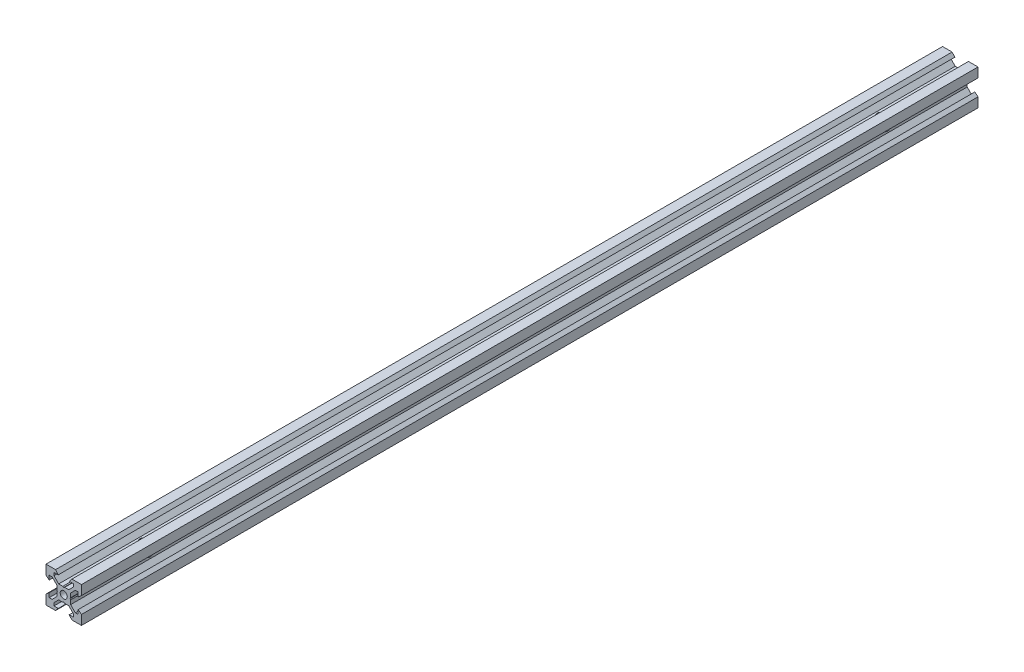
SolidWorks part; units mm, degrees
material "3.3535 (EN-AW 5754)"
ref_plane "Front Plane" through (0, 0, 0) normal (0, 0, 1) x (1, 0, 0)
ref_plane "Top Plane" through (0, 0, 0) normal (0, 1, 0) x (1, 0, 0)
ref_plane "Right Plane" through (0, 0, 0) normal (1, 0, 0) x (0, 0, -1)
sketch "Sketch1" plane through (0, 0, 0) normal (0, 0, 1) x (1, 0, 0)
  line L0 (10, 10) -> (4.6104, 10) construction
  line L1 (10, 10) -> (10, 4.6104) construction
  line L2 (10, -10) -> (10, -4.6104) construction
  line L3 (10, -10) -> (4.6104, -10) construction
  line L4 (10, 10) -> (10, 4.6104)
  line L5 (6.5607, 5.5) -> (8.2, 5.5)
  line L6 (5.5, 8.2) -> (5.5, 6.5607)
  line L7 (10, 10) -> (4.6104, 10)
  line L8 (10, 10) -> (10, 4.6104)
  line L9 (6.5607, 5.5) -> (3.9, 2.8393)
  line L10 (5.5, 6.5607) -> (2.8393, 3.9)
  line L11 (10, 4.6104) -> (8.2, 3.1)
  line L12 (4.6104, 10) -> (3.1, 8.2)
  line L13 (8.2, 3.1) -> (8.2, 5.5)
  line L14 (3.1, 8.2) -> (5.5, 8.2)
  line L15 (-6.5607, 5.5) -> (-8.2, 5.5)
  line L16 (6.5607, -5.5) -> (8.2, -5.5)
  line L17 (3.1, -8.2) -> (5.5, -8.2)
  line L18 (8.2, -3.1) -> (8.2, -5.5)
  line L19 (4.6104, -10) -> (3.1, -8.2)
  line L20 (10, -4.6104) -> (8.2, -3.1)
  line L21 (0.5196, -3.9) -> (0, -3.6)
  line L22 (0.5196, 3.9) -> (0, 3.6)
  line L23 (3.6, 0) -> (3.9, -0.5196)
  line L24 (3.9, 0.5196) -> (3.6, 0)
  line L25 (3.9, 0.5196) -> (3.9, 2.8393)
  line L26 (2.8393, 3.9) -> (0.5196, 3.9)
  line L27 (3.9, -2.8393) -> (3.9, -0.5196)
  line L28 (2.8393, -3.9) -> (0.5196, -3.9)
  line L29 (5.5, -6.5607) -> (2.8393, -3.9)
  line L30 (6.5607, -5.5) -> (3.9, -2.8393)
  line L31 (10, -10) -> (10, -4.6104)
  line L32 (10, -10) -> (4.6104, -10)
  line L33 (5.5, -8.2) -> (5.5, -6.5607)
  line L34 (-6.5607, -5.5) -> (-8.2, -5.5)
  line L35 (10, -10) -> (10, -4.6104)
  line L36 (0, 0) -> (0, 8.2) construction
  line L37 (-10, -10) -> (-4.6104, -10) construction
  line L38 (-10, -10) -> (-10, -4.6104) construction
  line L39 (-10, 10) -> (-10, 4.6104) construction
  line L40 (-10, 10) -> (-4.6104, 10) construction
  line L41 (-10, -10) -> (-10, -4.6104)
  line L43 (-5.5, -8.2) -> (-5.5, -6.5607)
  line L44 (-10, -10) -> (-4.6104, -10)
  line L45 (-10, -10) -> (-10, -4.6104)
  line L46 (-6.5607, -5.5) -> (-3.9, -2.8393)
  line L47 (-5.5, -6.5607) -> (-2.8393, -3.9)
  line L48 (-2.8393, -3.9) -> (-0.5196, -3.9)
  line L49 (-3.9, -2.8393) -> (-3.9, -0.5196)
  line L50 (-2.8393, 3.9) -> (-0.5196, 3.9)
  line L51 (-3.9, 0.5196) -> (-3.9, 2.8393)
  line L52 (-3.9, 0.5196) -> (-3.6, 0)
  line L53 (-3.6, 0) -> (-3.9, -0.5196)
  line L54 (-0.5196, 3.9) -> (0, 3.6)
  line L55 (-0.5196, -3.9) -> (0, -3.6)
  line L56 (-10, -4.6104) -> (-8.2, -3.1)
  line L57 (-4.6104, -10) -> (-3.1, -8.2)
  line L58 (-8.2, -3.1) -> (-8.2, -5.5)
  line L59 (-3.1, -8.2) -> (-5.5, -8.2)
  line L60 (-10, -10) -> (10, -10) construction
  line L61 (-10, -10) -> (-10, 10) construction
  line L62 (-3.1, 8.2) -> (-5.5, 8.2)
  line L63 (-8.2, 3.1) -> (-8.2, 5.5)
  line L64 (-4.6104, 10) -> (-3.1, 8.2)
  line L65 (-10, 4.6104) -> (-8.2, 3.1)
  line L66 (-5.5, 6.5607) -> (-2.8393, 3.9)
  line L67 (-6.5607, 5.5) -> (-3.9, 2.8393)
  line L68 (-10, 10) -> (-10, 4.6104)
  line L69 (-10, 10) -> (-4.6104, 10)
  line L70 (-5.5, 8.2) -> (-5.5, 6.5607)
  line L71 (-10, 10) -> (10, 10) construction
  line L72 (-10, 10) -> (-10, 4.6104)
  line L73 (10, -10) -> (10, 10) construction
  line L74 (-10, -10) -> (10, 10) construction
  line L75 (-10, 10) -> (10, -10) construction
  circle A0 centre (0, 0) radius 2
  dimension "D7" = 4
  dimension "D1" = 20
  dimension "D2" = 5.3896
  dimension "D3" = 4.5
  dimension "D4" = 50
  dimension "D5" = 1.8
  dimension "D6" = 1.5104
  dimension "D8" = 5.5
  dimension "D9" = 120
  dimension "D10" = 0.3
  dimension "D11" = 2.3197
  dimension "D12" = 7.8
  dimension "D13" = 7.8
  dimension "D14" = 1.5
  dimension "D15" = 2.6607
extrude "Boss-Extrude1" add sketch "Sketch1" along normal blind 506 contours L70 L62 L64 L69 L68 L65 L63 L15 L67 L51 L52 L53 L49 L46 L34 L58 L56 L41 L44 L57 L59 L43 L47 L48 L55 L21 L28 L29 L33 L17 L19 L32 L31 L20 L18 L16 L30 L27 L23 L24 L25 L9 L5 L13 L11 L4 L7 L12 L14 L6 L10
sketch "Sketch2" plane through (0, -3.9, 0) normal (0, -1, 0) x (-1, 0, 0)
  line L0 (0, -506) -> (0, -461) construction
  line L1 (0, -506) -> (0, 0) construction
  line L2 (0, 0) -> (0, -45) construction
  circle A0 centre (0, -461) radius 2
  circle A1 centre (0, -45) radius 2
  dimension "D2" = 4
  dimension "D4" = 4
  dimension "D1" = 45
  dimension "D3" = 45
extrude "Cut-Extrude1" cut sketch "Sketch2" against normal through all both and the other way through all
sketch "Sketch3" plane through (3.9, 0, 0) normal (1, 0, 0) x (0, 0, -1)
  line L0 (0, 0) -> (-45, 0) construction
  line L1 (-506, 0) -> (0, 0) construction
  line L2 (-506, 0) -> (-461, 0) construction
  circle A0 centre (-45, 0) radius 2
  circle A1 centre (-461, 0) radius 2
  dimension "D2" = 4
  dimension "D4" = 4
  dimension "D1" = 45
  dimension "D3" = 45
extrude "Cut-Extrude2" cut sketch "Sketch3" against normal through all both
